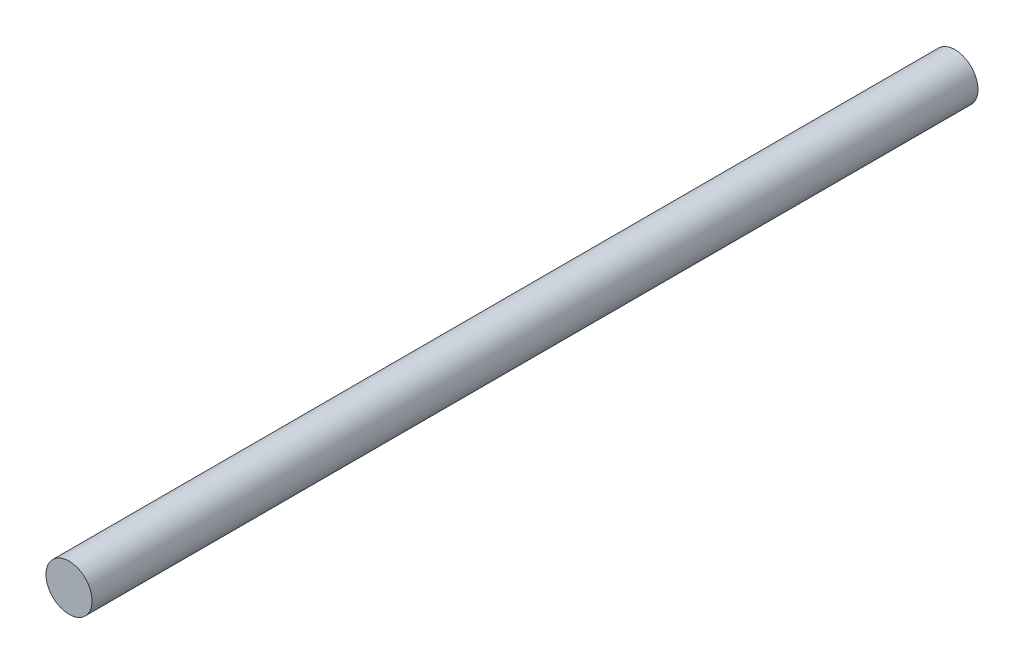
SolidWorks part; units mm, degrees
material "Plain Carbon Steel"
ref_plane "Front Plane" through (0, 0, 0) normal (0, 0, 1) x (1, 0, 0)
ref_plane "Top Plane" through (0, 0, 0) normal (0, 1, 0) x (1, 0, 0)
ref_plane "Right Plane" through (0, 0, 0) normal (1, 0, 0) x (0, 0, -1)
sketch "Sketch2" plane through (0, 0, 0) normal (0, 0, 1) x (1, 0, 0)
  circle A0 centre (0, 0) radius 2.5
  dimension "D1" = 5
extrude "Boss-Extrude1" add sketch "Sketch2" along normal mid plane 96
